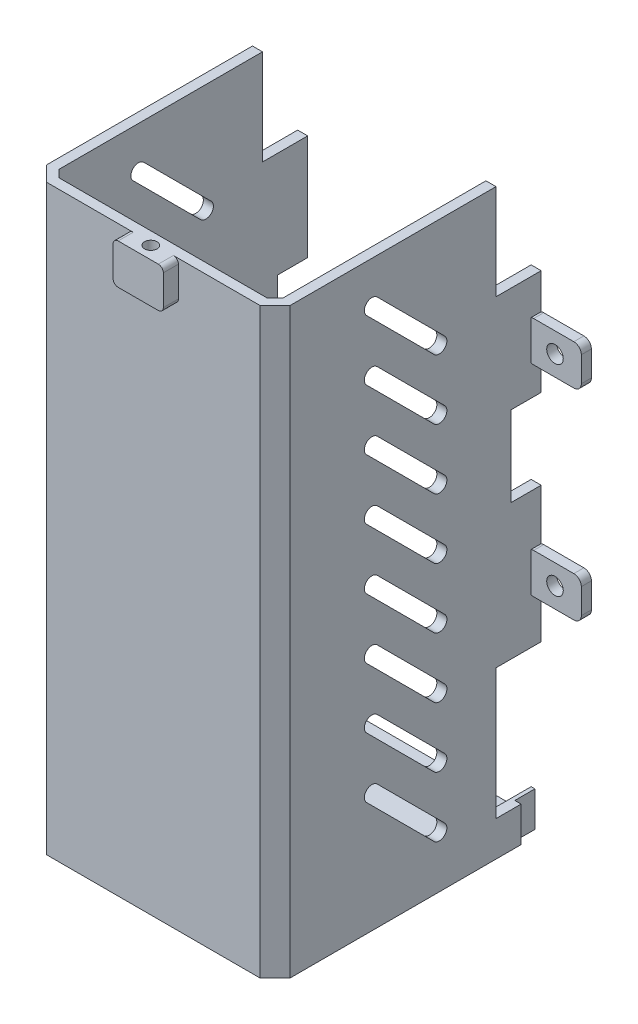
SolidWorks part; units mm, degrees
material "镁合金_CNC_暂定1800kg_m3"
ref_plane "前视基准面" through (0, 0, 0) normal (0, 0, 1) x (1, 0, 0)
ref_plane "上视基准面" through (0, 0, 0) normal (0, 1, 0) x (1, 0, 0)
ref_plane "右视基准面" through (0, 0, 0) normal (1, 0, 0) x (0, 0, -1)
other "Configuration Table"
sketch "草图1" plane through (0, 0, 0) normal (0, 1, 0) x (1, 0, 0)
  line L0 (-24.25, -3) -> (-24.25, -53)
  line L1 (-24.25, -53) -> (-21.25, -56)
  line L2 (-21.25, -56) -> (21.25, -56)
  line L3 (21.25, -56) -> (24.25, -53)
  line L4 (24.25, -53) -> (24.25, -3)
  line L5 (24.25, -3) -> (22.25, -3)
  line L6 (22.25, -3) -> (22.25, -52.5)
  line L7 (22.25, -52.5) -> (20.75, -54)
  line L8 (20.75, -54) -> (-20.75, -54)
  line L9 (-20.75, -54) -> (-22.25, -52.5)
  line L10 (-22.25, -52.5) -> (-22.25, -3)
  line L11 (-22.25, -3) -> (-24.25, -3)
extrude "后抽U形电池仓_2mm主壁_斜切肩" add sketch "草图1" along normal blind 116 from offset 26
sketch "草图2" plane through (0, 0, 0) normal (0, 1, 0) x (1, 0, 0)
  line L0 (-24.25, -3) -> (-24.25, -53)
  line L1 (-24.25, -53) -> (-21.25, -56)
  line L2 (-21.25, -56) -> (21.25, -56)
  line L3 (21.25, -56) -> (24.25, -53)
  line L4 (24.25, -53) -> (24.25, -3)
  line L5 (24.25, -3) -> (-24.25, -3)
extrude "前端封闭触点预留壁" add sketch "草图2" along normal blind 2 from offset 26
sketch "草图3" plane through (0, 0, 0) normal (0, 0, 1) x (1, 0, 0)
  line L0 (-32.75, 16) -> (-24.75, 16)
  line L1 (-23.25, 17.5) -> (-23.25, 22.5)
  line L2 (-24.75, 24) -> (-32.75, 24)
  line L3 (-34.25, 22.5) -> (-34.25, 17.5)
  arc A0 (-24.75, 16) -> (-23.25, 17.5) centre (-24.75, 17.5) ccw
  arc A1 (-23.25, 22.5) -> (-24.75, 24) centre (-24.75, 22.5) ccw
  arc A2 (-32.75, 24) -> (-34.25, 22.5) centre (-32.75, 22.5) ccw
  arc A3 (-34.25, 17.5) -> (-32.75, 16) centre (-32.75, 17.5) ccw
  circle A4 centre (-29, 20) radius 1.65
extrude "M3底脚_-1_20" add sketch "草图3" along normal blind 2 from offset 3
sketch "草图4" plane through (0, 0, 0) normal (0, 0, 1) x (1, 0, 0)
  line L0 (-32.75, 56) -> (-24.75, 56)
  line L1 (-23.25, 57.5) -> (-23.25, 62.5)
  line L2 (-24.75, 64) -> (-32.75, 64)
  line L3 (-34.25, 62.5) -> (-34.25, 57.5)
  arc A0 (-24.75, 56) -> (-23.25, 57.5) centre (-24.75, 57.5) ccw
  arc A1 (-23.25, 62.5) -> (-24.75, 64) centre (-24.75, 62.5) ccw
  arc A2 (-32.75, 64) -> (-34.25, 62.5) centre (-32.75, 62.5) ccw
  arc A3 (-34.25, 57.5) -> (-32.75, 56) centre (-32.75, 57.5) ccw
  circle A4 centre (-29, 60) radius 1.65
extrude "M3底脚_-1_60" add sketch "草图4" along normal blind 2 from offset 3
sketch "草图5" plane through (0, 0, 0) normal (0, 0, 1) x (1, 0, 0)
  line L0 (24.75, 16) -> (32.75, 16)
  line L1 (34.25, 17.5) -> (34.25, 22.5)
  line L2 (32.75, 24) -> (24.75, 24)
  line L3 (23.25, 22.5) -> (23.25, 17.5)
  arc A0 (32.75, 16) -> (34.25, 17.5) centre (32.75, 17.5) ccw
  arc A1 (34.25, 22.5) -> (32.75, 24) centre (32.75, 22.5) ccw
  arc A2 (24.75, 24) -> (23.25, 22.5) centre (24.75, 22.5) ccw
  arc A3 (23.25, 17.5) -> (24.75, 16) centre (24.75, 17.5) ccw
  circle A4 centre (29, 20) radius 1.65
extrude "M3底脚_1_20" add sketch "草图5" along normal blind 2 from offset 3
sketch "草图6" plane through (0, 0, 0) normal (0, 0, 1) x (1, 0, 0)
  line L0 (24.75, 56) -> (32.75, 56)
  line L1 (34.25, 57.5) -> (34.25, 62.5)
  line L2 (32.75, 64) -> (24.75, 64)
  line L3 (23.25, 62.5) -> (23.25, 57.5)
  arc A0 (32.75, 56) -> (34.25, 57.5) centre (32.75, 57.5) ccw
  arc A1 (34.25, 62.5) -> (32.75, 64) centre (32.75, 62.5) ccw
  arc A2 (24.75, 64) -> (23.25, 62.5) centre (24.75, 62.5) ccw
  arc A3 (23.25, 57.5) -> (24.75, 56) centre (24.75, 57.5) ccw
  circle A4 centre (29, 60) radius 1.65
extrude "M3底脚_1_60" add sketch "草图6" along normal blind 2 from offset 3
sketch "草图7" plane through (0, 0, 0) normal (0, 0, 1) x (1, 0, 0)
  line L0 (-33, -19) -> (33, -19)
  line L1 (35, -17) -> (35, 5)
  line L2 (33, 7) -> (-33, 7)
  line L3 (-35, 5) -> (-35, -17)
  line L4 (-33, 71) -> (33, 71)
  line L5 (35, 73) -> (35, 95)
  line L6 (33, 97) -> (-33, 97)
  line L7 (-35, 95) -> (-35, 73)
  arc A0 (33, -19) -> (35, -17) centre (33, -17) ccw
  arc A1 (35, 5) -> (33, 7) centre (33, 5) ccw
  arc A2 (-33, 7) -> (-35, 5) centre (-33, 5) ccw
  arc A3 (-35, -17) -> (-33, -19) centre (-33, -17) ccw
  arc A4 (33, 71) -> (35, 73) centre (33, 73) ccw
  arc A5 (35, 95) -> (33, 97) centre (33, 95) ccw
  arc A6 (-33, 97) -> (-35, 95) centre (-33, 95) ccw
  arc A7 (-35, 73) -> (-33, 71) centre (-33, 73) ccw
extrude "保留扎带孔的下缘通道" cut sketch "草图7" along normal blind 9 from offset 3
sketch "草图8" plane through (0, 0, 0) normal (0, 0, 1) x (1, 0, 0)
  line L0 (-25, 34) -> (25, 34)
  line L1 (27, 36) -> (27, 48)
  line L2 (25, 50) -> (-25, 50)
  line L3 (-27, 48) -> (-27, 36)
  arc A0 (25, 34) -> (27, 36) centre (25, 36) ccw
  arc A1 (27, 48) -> (25, 50) centre (25, 48) ccw
  arc A2 (-25, 50) -> (-27, 48) centre (-25, 48) ccw
  arc A3 (-27, 36) -> (-25, 34) centre (-25, 36) ccw
extrude "斜机臂根部一毫米净空" cut sketch "草图8" along normal blind 6 from offset 3
sketch "草图9" plane through (0, 0, 0) normal (1, 0, 0) x (0, 0, -1)
  line L0 (-22.2218, -14.6569) -> (-35.6569, -1.2218)
  line L1 (-37.7782, -3.3431) -> (-24.3431, -16.7782)
  line L2 (-22.2218, -2.6569) -> (-35.6569, 10.7782)
  line L3 (-37.7782, 8.6569) -> (-24.3431, -4.7782)
  line L4 (-22.2218, 9.3431) -> (-35.6569, 22.7782)
  line L5 (-37.7782, 20.6569) -> (-24.3431, 7.2218)
  line L6 (-22.2218, 21.3431) -> (-35.6569, 34.7782)
  line L7 (-37.7782, 32.6569) -> (-24.3431, 19.2218)
  line L8 (-22.2218, 33.3431) -> (-35.6569, 46.7782)
  line L9 (-37.7782, 44.6569) -> (-24.3431, 31.2218)
  line L10 (-22.2218, 45.3431) -> (-35.6569, 58.7782)
  line L11 (-37.7782, 56.6569) -> (-24.3431, 43.2218)
  line L12 (-22.2218, 57.3431) -> (-35.6569, 70.7782)
  line L13 (-37.7782, 68.6569) -> (-24.3431, 55.2218)
  line L14 (-22.2218, 69.3431) -> (-35.6569, 82.7782)
  line L15 (-37.7782, 80.6569) -> (-24.3431, 67.2218)
  arc A0 (-35.6569, -1.2218) -> (-37.7782, -3.3431) centre (-36.7175, -2.2825) ccw
  arc A1 (-24.3431, -16.7782) -> (-22.2218, -14.6569) centre (-23.2825, -15.7175) ccw
  arc A2 (-35.6569, 10.7782) -> (-37.7782, 8.6569) centre (-36.7175, 9.7175) ccw
  arc A3 (-24.3431, -4.7782) -> (-22.2218, -2.6569) centre (-23.2825, -3.7175) ccw
  arc A4 (-35.6569, 22.7782) -> (-37.7782, 20.6569) centre (-36.7175, 21.7175) ccw
  arc A5 (-24.3431, 7.2218) -> (-22.2218, 9.3431) centre (-23.2825, 8.2825) ccw
  arc A6 (-35.6569, 34.7782) -> (-37.7782, 32.6569) centre (-36.7175, 33.7175) ccw
  arc A7 (-24.3431, 19.2218) -> (-22.2218, 21.3431) centre (-23.2825, 20.2825) ccw
  arc A8 (-35.6569, 46.7782) -> (-37.7782, 44.6569) centre (-36.7175, 45.7175) ccw
  arc A9 (-24.3431, 31.2218) -> (-22.2218, 33.3431) centre (-23.2825, 32.2825) ccw
  arc A10 (-35.6569, 58.7782) -> (-37.7782, 56.6569) centre (-36.7175, 57.7175) ccw
  arc A11 (-24.3431, 43.2218) -> (-22.2218, 45.3431) centre (-23.2825, 44.2825) ccw
  arc A12 (-35.6569, 70.7782) -> (-37.7782, 68.6569) centre (-36.7175, 69.7175) ccw
  arc A13 (-24.3431, 55.2218) -> (-22.2218, 57.3431) centre (-23.2825, 56.2825) ccw
  arc A14 (-35.6569, 82.7782) -> (-37.7782, 80.6569) centre (-36.7175, 81.7175) ccw
  arc A15 (-24.3431, 67.2218) -> (-22.2218, 69.3431) centre (-23.2825, 68.2825) ccw
extrude "两侧45度平行短通风槽" cut sketch "草图9" along normal blind 60 and the other way blind 60
sketch "草图10" plane through (0, 0, 0) normal (0, 0, 1) x (1, 0, 0)
  line L0 (-4, 82) -> (4, 82)
  line L1 (5, 83) -> (5, 89)
  line L2 (4, 90) -> (-4, 90)
  line L3 (-5, 89) -> (-5, 83)
  arc A0 (4, 82) -> (5, 83) centre (4, 83) ccw
  arc A1 (5, 89) -> (4, 90) centre (4, 89) ccw
  arc A2 (-4, 90) -> (-5, 89) centre (-4, 89) ccw
  arc A3 (-5, 83) -> (-4, 82) centre (-4, 83) ccw
extrude "后门手拧锁扣一体安装脊" add sketch "草图10" along normal blind 5 from offset 54
sketch "草图11" plane through (0, 0, 0) normal (0, 1, 0) x (1, 0, 0)
  circle A0 centre (0, -56.5) radius 1.25
extrude "M3后门锁扣盲孔_深7" cut sketch "草图11" along normal blind 7 from offset 83
sketch "草图12" plane through (0, 0, 0) normal (0, 0, 1) x (1, 0, 0)
  line L0 (-33, -29) -> (-25, -29)
  line L1 (-23, -27) -> (-23, -19)
  line L2 (-25, -17) -> (-33, -17)
  line L3 (-35, -19) -> (-35, -27)
  line L4 (25, -29) -> (33, -29)
  line L5 (35, -27) -> (35, -19)
  line L6 (33, -17) -> (25, -17)
  line L7 (23, -19) -> (23, -27)
  arc A0 (-25, -29) -> (-23, -27) centre (-25, -27) ccw
  arc A1 (-23, -19) -> (-25, -17) centre (-25, -19) ccw
  arc A2 (-33, -17) -> (-35, -19) centre (-33, -19) ccw
  arc A3 (-35, -27) -> (-33, -29) centre (-33, -27) ccw
  arc A4 (33, -29) -> (35, -27) centre (33, -27) ccw
  arc A5 (35, -19) -> (33, -17) centre (33, -19) ccw
  arc A6 (25, -17) -> (23, -19) centre (25, -19) ccw
  arc A7 (23, -27) -> (25, -29) centre (25, -27) ccw
extrude "前下角雷达底脚半毫米避让" cut sketch "草图12" along normal blind 4 from offset 3
